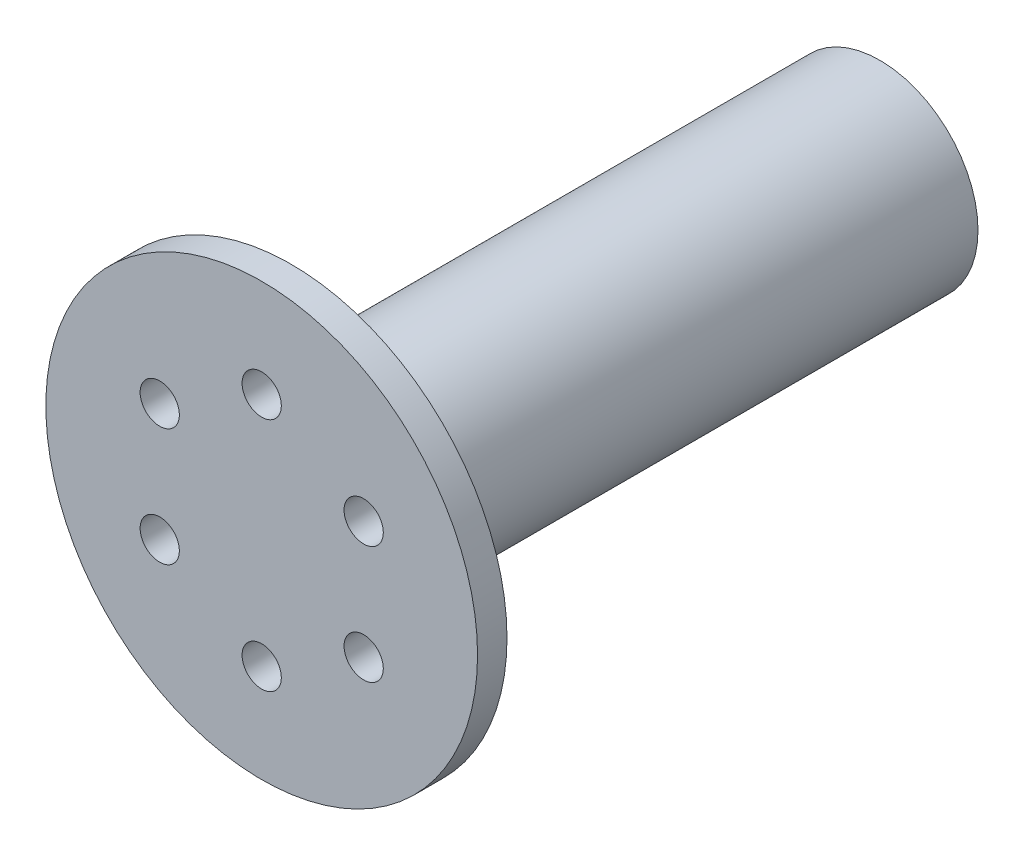
SolidWorks part; units mm, degrees
ref_plane "Front Plane" through (0, 0, 0) normal (0, 0, 1) x (1, 0, 0)
ref_plane "Top Plane" through (0, 0, 0) normal (0, 1, 0) x (1, 0, 0)
ref_plane "Right Plane" through (0, 0, 0) normal (1, 0, 0) x (0, 0, -1)
sketch "Sketch1" plane through (0, 0, 0) normal (0, 0, 1) x (1, 0, 0)
  circle A0 centre (0, 0) radius 5
  dimension "D1" = 10
extrude "Boss-Extrude1" add sketch "Sketch1" along normal blind 30
sketch "Sketch2" plane through (0, 0, 0) normal (0, 0, -1) x (-1, 0, 0)
  line L6 (-0.5, -1.4142) -> (-0.5, -2.514)
  line L7 (-0.5, -2.514) -> (0.5, -2.514)
  line L8 (0.5, -1.4142) -> (0.5, -2.514)
  arc A1 (0.5, -1.4142) -> (-0.5, -1.4142) centre (0, 0) ccw
  point P3 (0, -1.5)
  dimension "D1" = 3
  dimension "D3" = 1
extrude "Cut-Extrude1" cut sketch "Sketch2" against normal blind 20
sketch "Sketch3" plane through (0, 0, 30) normal (0, 0, 1) x (1, 0, 0)
  circle A1 centre (0, 0) radius 11
  dimension "D1" = 22
extrude "Boss-Extrude2" add sketch "Sketch3" along normal blind 1.5
sketch "Sketch4" plane through (0, 0, 31.5) normal (0, 0, 1) x (1, 0, 0)
  circle A0 centre (0, 0) radius 6 construction
  circle A1 centre (0, 6) radius 1
  circle A2 centre (5.1962, 3) radius 1
  circle A3 centre (5.1962, -3) radius 1
  circle A4 centre (0, -6) radius 1
  circle A5 centre (-5.1962, -3) radius 1
  circle A6 centre (-5.1962, 3) radius 1
  point P18 (0, 0)
  dimension "D1" = 12
  dimension "D2" = 2
  dimension "D3" = 6
extrude "Cut-Extrude2" cut sketch "Sketch4" against normal blind 1.5
